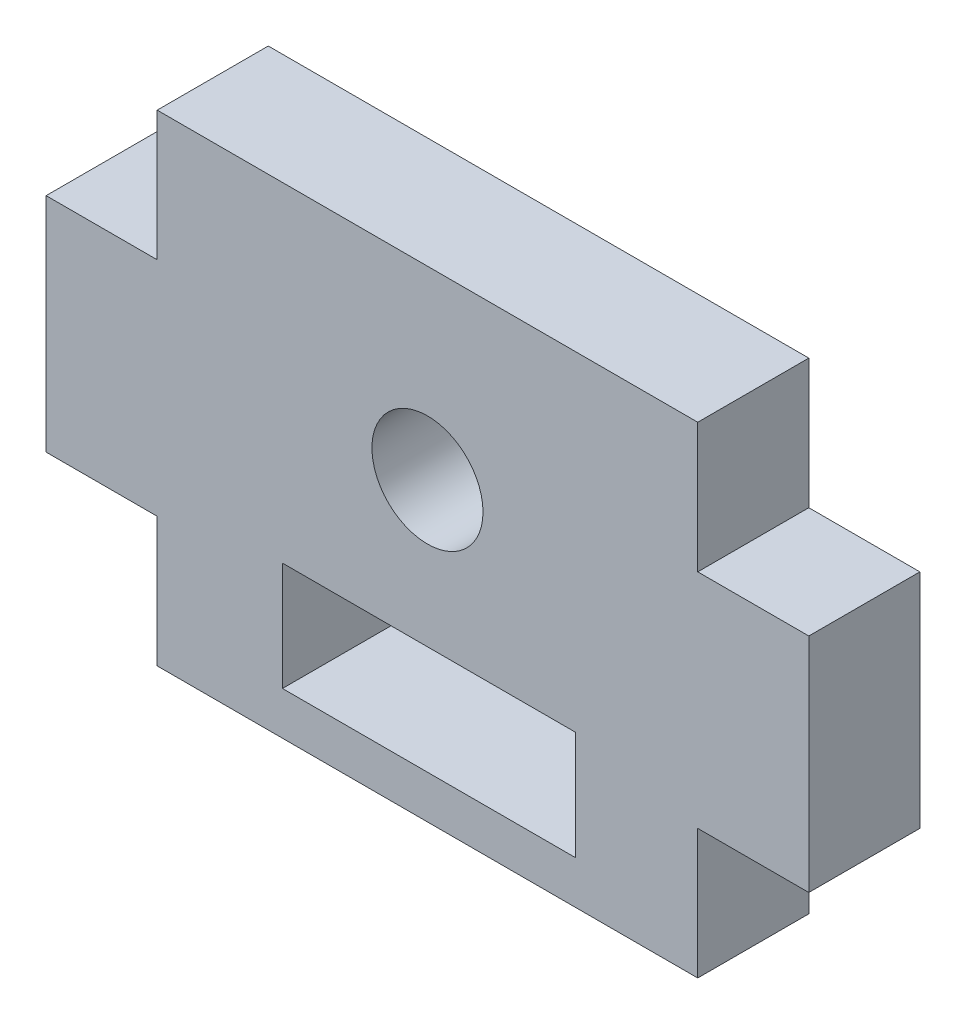
SolidWorks part; units mm, degrees
material "Balsa"
ref_plane "Alzado" through (0, 0, 0) normal (0, 0, 1) x (1, 0, 0)
ref_plane "Planta" through (0, 0, 0) normal (0, 1, 0) x (1, 0, 0)
ref_plane "Vista lateral" through (0, 0, 0) normal (1, 0, 0) x (0, 0, -1)
sketch "Croquis1" plane through (0, 0, 0) normal (0, 0, 1) x (1, 0, 0)
  line L1 (-7.3, -6.5) -> (7.3, -6.5)
  line L2 (-7.3, -6.5) -> (-7.3, 6.5)
  line L3 (-7.3, 6.5) -> (7.3, 6.5)
  line L4 (7.3, -6.5) -> (7.3, 6.5)
  line L5 (-7.3, -6.5) -> (7.3, 6.5) construction
  line L6 (-7.3, 6.5) -> (7.3, -6.5) construction
  line L7 (-7.3, -3) -> (-10.3, -3)
  line L8 (-7.3, -3) -> (-7.3, 3)
  line L9 (-7.3, 3) -> (-10.3, 3)
  line L10 (-10.3, -3) -> (-10.3, 3)
  line L11 (7.3, -3) -> (10.3, -3)
  line L12 (7.3, -3) -> (7.3, 3)
  line L13 (7.3, 3) -> (10.3, 3)
  line L14 (10.3, -3) -> (10.3, 3)
  point P0 (0, 0)
  dimension "D1" = 14.6
  dimension "D2" = 3
  dimension "D3" = 3
  dimension "D4" = 13
  dimension "D5" = 6
  dimension "D6" = 6
  dimension "D7" = 3
  dimension "D8" = 3
extrude "Saliente-Extruir1" add sketch "Croquis1" along normal blind 3 contours L1 L4 L3 L2 | L10 L7 L2 L9 | L11 L14 L13 L4
sketch "Croquis2" plane through (0, 0, 3) normal (0, 0, 1) x (1, 0, 0)
  line L1 (-3.9166, -2.4031) -> (3.9934, -2.4031)
  line L2 (-3.9166, -2.4031) -> (-3.9166, -5.3363)
  line L3 (-3.9166, -5.3363) -> (3.9934, -5.3363)
  line L4 (3.9934, -2.4031) -> (3.9934, -5.3363)
  circle A0 centre (0, 1.5) radius 1.5
extrude "Cortar-Extruir1" cut sketch "Croquis2" against normal blind 10
